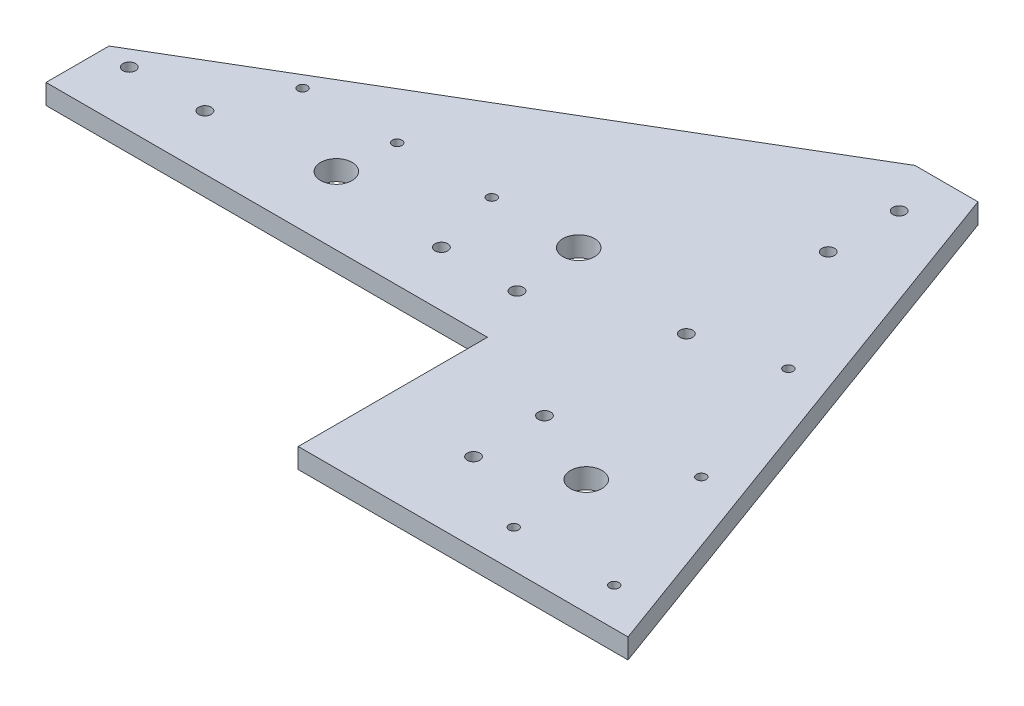
SolidWorks part; units mm, degrees
ref_plane "Front" through (0, 0, 0) normal (0, 0, 1) x (1, 0, 0)
ref_plane "Top" through (0, 0, 0) normal (0, 1, 0) x (1, 0, 0)
ref_plane "Right" through (0, 0, 0) normal (1, 0, 0) x (0, 0, -1)
sketch "Sketch1" plane through (0, 0, 0) normal (0, 1, 0) x (1, 0, 0)
  line L0 (145, 175) -> (180.6, 175)
  line L1 (0, 0) -> (145, 0)
  line L2 (0, 0) -> (0, 175)
  line L3 (0, 175) -> (145, 175)
  line L4 (145, 0) -> (145, 175)
  line L5 (180.6, 175) -> (180.6, 0)
  line L6 (180.6, 0) -> (145, 0)
  line L7 (145, 0) -> (145, 60)
  line L8 (145, 60) -> (140, 60)
  line L9 (140, 60) -> (140, 0)
  line L10 (140, 60) -> (0, 60)
  line L11 (180.6, 175) -> (160.6, 175)
  line L12 (0, 60) -> (0, 80)
  line L13 (160.6, 175) -> (0, 80)
  line L14 (0, 60) -> (70.5, 60)
  line L15 (70.5, 60) -> (70.5, 81.59)
  line L16 (70.5, 81.59) -> (129.875, 81.59)
  line L17 (180.6, 0) -> (244.6, 0)
  line L18 (244.6, 0) -> (180.6, 175)
  line L19 (129.875, 81.59) -> (129.875, 99.09)
  line L20 (244.6, 0) -> (194.75, 0)
  line L21 (194.75, 0) -> (194.75, 36.59)
  circle A0 centre (70.5, 81.59) radius 5
  circle A2 centre (129.875, 99.09) radius 5
  circle A3 centre (194.75, 36.59) radius 5
  dimension "D10" = 59.375
  dimension "D11" = 64
  dimension "D13" = 36.59
  dimension "D1" = 175
  dimension "D2" = 145
  dimension "D3" = 35.6
  dimension "D4" = 60
  dimension "D5" = 5
  dimension "D6" = 20
  dimension "D7" = 20
  dimension "D8" = 70.5
  dimension "D9" = 21.59
  dimension "D12" = 17.5
  dimension "D14" = 49.85
extrude "Boss-Extrude2" add sketch "Sketch1" along normal blind 6.35
sketch "Sketch3" plane through (0, 6.35, 0) normal (0, 1, 0) x (1, 0, 0)
  line L0 (0, 60) -> (0, 99.0944)
  line L1 (0, 99.0944) -> (42.2796, 99.0944)
  line L2 (42.2796, 99.0944) -> (32.2796, 99.0944)
  line L3 (160.6, 175) -> (0, 80) construction
  line L4 (42.2796, 99.0944) -> (72.2796, 99.0944)
  line L5 (72.2796, 99.0944) -> (102.2796, 99.0944)
  line L6 (102.2796, 99.0944) -> (208.3598, 99.0944)
  line L7 (244.6, 0) -> (180.6, 175) construction
  line L8 (208.3598, 99.0944) -> (196.3598, 99.0944)
  line L9 (244.6, 0) -> (232.0087, 0)
  line L10 (244.6, 0) -> (140, 0) construction
  line L11 (240.2114, 12) -> (228.2114, 12)
  line L12 (228.2114, 12) -> (232.0087, 12)
  line L13 (232.0087, 12) -> (232.0087, 0)
  line L14 (196.3598, 99.0944) -> (228.2114, 12)
  line L15 (228.2114, 12) -> (212.2856, 55.5472)
  line L16 (212.2856, 55.5472) -> (196.3598, 99.0944)
  line L17 (228.2114, 12) -> (196.3598, 12)
  circle A0 centre (42.2796, 99.0944) radius 1.5
  circle A1 centre (72.2796, 99.0944) radius 1.5
  circle A2 centre (102.2796, 99.0944) radius 1.5
  circle A3 centre (196.3598, 99.0944) radius 1.5
  circle A4 centre (212.2856, 55.5472) radius 1.5
  circle A5 centre (228.2114, 12) radius 1.5
  circle A6 centre (196.3598, 12) radius 1.5
  dimension "D5" = 12
  dimension "D6" = 12
  dimension "D1" = 39.0944
  dimension "D2" = 10
  dimension "D3" = 30
  dimension "D4" = 30
  dimension "D7" = 12
extrude "Cut-Extrude1" cut sketch "Sketch3" against normal blind 6.35
sketch "Sketch4" plane through (0, 6.35, 0) normal (0, 1, 0) x (1, 0, 0)
  line L0 (170.6, 175) -> (170.6, 137.5)
  line L1 (160.6, 175) -> (180.6, 175) construction
  line L2 (170.6, 137.5) -> (170.6, 92.5)
  line L3 (170.6, 92.5) -> (170.6, 47.5)
  line L4 (170.6, 160) -> (170.6, 25)
  circle A0 centre (170.6, 137.5) radius 2
  circle A1 centre (170.6, 92.5) radius 2
  circle A2 centre (170.6, 47.5) radius 2
  circle A3 centre (170.6, 160) radius 2
  circle A4 centre (170.6, 25) radius 2
  dimension "D4" = 15
  dimension "D1" = 37.5
  dimension "D2" = 45
  dimension "D3" = 45
  dimension "D5" = 135
extrude "Cut-Extrude2" cut sketch "Sketch4" against normal blind 10 contours L0 A3 | L0 A3 | A0 | A1 | A2 | A4
sketch "Sketch6" plane through (0, 0, 0) normal (0, -1, 0) x (-1, 0, 0)
  line L0 (-33, 77.4) -> (-9, 77.4)
  circle A0 centre (-132, 77.4) radius 2
  circle A1 centre (-108, 77.4) radius 2
  circle A2 centre (-33, 77.4) radius 2
  circle A3 centre (-33, 77.4) radius 2
  circle A4 centre (-9, 77.4) radius 2
  dimension "D1" = 24
extrude "Cut-Extrude3" cut sketch "Sketch6" against normal blind 6.35 contours A2 | A4 | A1 | A0
sketch "Sketch7" plane through (0, 6.35, 0) normal (0, 1, 0) x (1, 0, 0)
  circle A0 centre (9, 77.4) radius 8
  circle A1 centre (42.2796, 99.0944) radius 7.5
  circle A2 centre (33, 77.4) radius 7.5
  circle A3 centre (72.2796, 99.0944) radius 7.5
  circle A4 centre (70.5, 81.59) radius 12.5
  circle A5 centre (102.2796, 99.0944) radius 7.5
  circle A6 centre (108, 77.4) radius 8
  circle A7 centre (132, 77.4) radius 8
  circle A8 centre (129.875, 99.09) radius 12.5
  circle A9 centre (170.6, 160) radius 8
  circle A10 centre (170.6, 137.5) radius 8
  circle A11 centre (170.6, 92.5) radius 8
  circle A12 centre (196.3598, 99.0944) radius 7.5
  circle A13 centre (170.6, 47.5) radius 8
  circle A14 centre (194.75, 36.59) radius 12.5
  circle A15 centre (170.6, 25) radius 8
  circle A16 centre (196.3598, 12) radius 7.5
  circle A17 centre (212.2856, 55.5472) radius 7.5
  circle A18 centre (228.2114, 12) radius 7.5
  dimension "D1" = 15
  dimension "D2" = 16
  dimension "D3" = 15
  dimension "D4" = 25
  dimension "D5" = 15
  dimension "D6" = 15
  dimension "D7" = 25
  dimension "D8" = 16
  dimension "D9" = 16
  dimension "D10" = 16
  dimension "D11" = 16
  dimension "D12" = 16
  dimension "D13" = 15
  dimension "D14" = 16
  dimension "D15" = 16
  dimension "D16" = 25
  dimension "D17" = 15
  dimension "D18" = 15
  dimension "D19" = 15
equation "\"r1\"=10"
equation "\"r2\"=12"
equation "\"r3\"=25"
